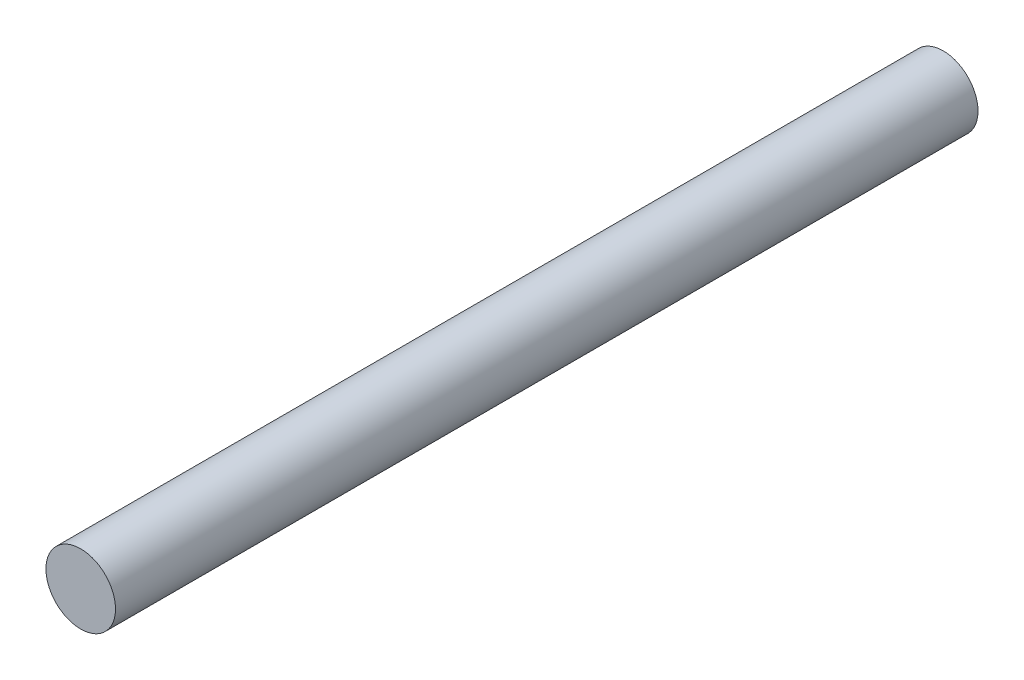
SolidWorks part; units mm, degrees
ref_plane "Спереди" through (0, 0, 0) normal (0, 0, 1) x (1, 0, 0)
ref_plane "Сверху" through (0, 0, 0) normal (0, 1, 0) x (1, 0, 0)
ref_plane "Справа" through (0, 0, 0) normal (1, 0, 0) x (0, 0, -1)
sketch "Эскиз1" plane through (0, 0, 0) normal (0, 0, 1) x (1, 0, 0)
  circle A0 centre (0, 0) radius 2.5
  dimension "D1" = 5
extrude "Бобышка-Вытянуть1" add sketch "Эскиз1" along normal blind 62
